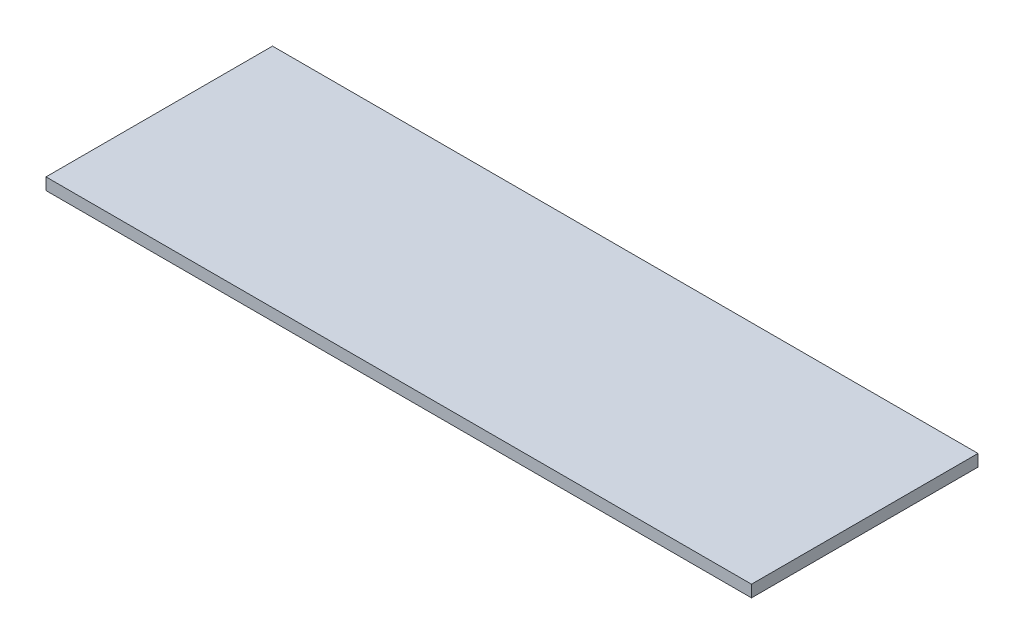
SolidWorks part; units mm, degrees
ref_plane "Front Plane" through (0, 0, 0) normal (0, 0, 1) x (1, 0, 0)
ref_plane "Top Plane" through (0, 0, 0) normal (0, 1, 0) x (1, 0, 0)
ref_plane "Right Plane" through (0, 0, 0) normal (1, 0, 0) x (0, 0, -1)
sketch "Sketch1" plane through (0, 0, 0) normal (0, 1, 0) x (1, 0, 0)
  line L1 (95, 30.5) -> (-95, 30.5)
  line L2 (95, 30.5) -> (95, -30.5)
  line L3 (95, -30.5) -> (-95, -30.5)
  line L4 (-95, 30.5) -> (-95, -30.5)
  line L5 (95, 30.5) -> (-95, -30.5) construction
  line L6 (95, -30.5) -> (-95, 30.5) construction
  point P0 (0, 0)
  dimension "D1" = 190
  dimension "D2" = 61
extrude "Boss-Extrude1" add sketch "Sketch1" along normal blind 3.2
